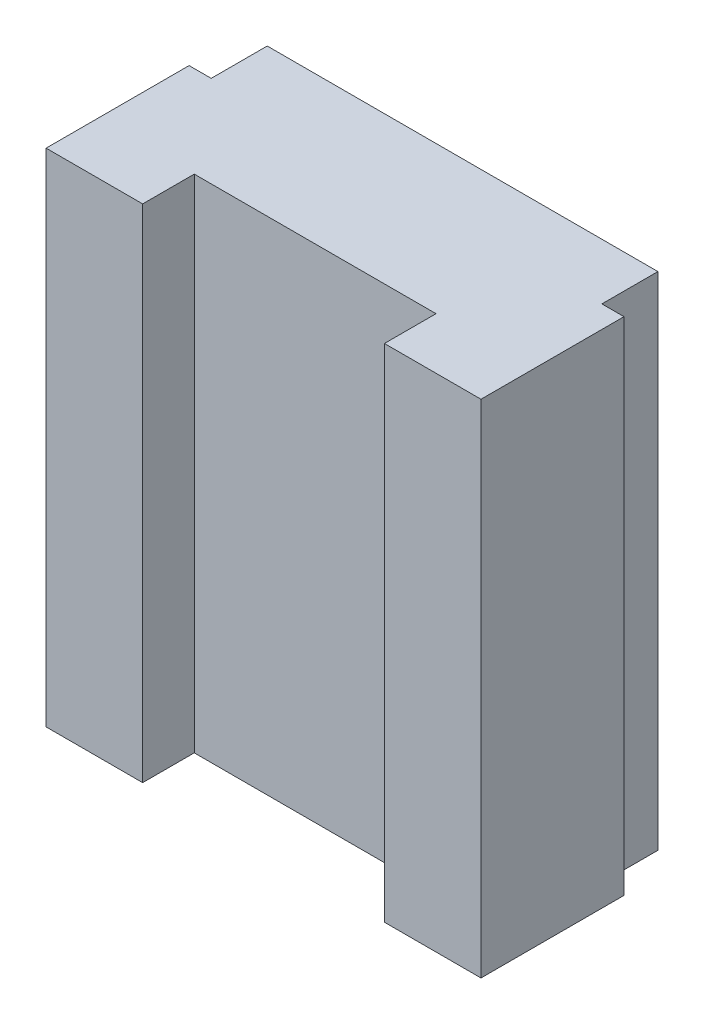
SolidWorks part; units mm, degrees
ref_plane "Front Plane" through (0, 0, 0) normal (0, 0, 1) x (1, 0, 0)
ref_plane "Top Plane" through (0, 0, 0) normal (0, 1, 0) x (1, 0, 0)
ref_plane "Right Plane" through (0, 0, 0) normal (1, 0, 0) x (0, 0, -1)
sketch "Sketch1" plane through (0, 0, 0) normal (0, 0, 1) x (1, 0, 0)
  line L1 (-14.75, 17) -> (14.75, 17)
  line L2 (-14.75, 17) -> (-14.75, -17)
  line L3 (-14.75, -17) -> (14.75, -17)
  line L4 (14.75, 17) -> (14.75, -17)
  line L5 (-14.75, 17) -> (14.75, -17) construction
  line L6 (-14.75, -17) -> (14.75, 17) construction
  point P0 (0, 0)
  dimension "D1" = 29.5
  dimension "D2" = 34
extrude "Boss-Extrude1" add sketch "Sketch1" along normal blind 13.5
sketch "Sketch2" plane through (0, 17, 0) normal (0, 1, 0) x (1, 0, 0)
  line L0 (-14.75, 0) -> (-14.75, -3.8)
  line L1 (-14.75, -13.5) -> (-14.75, 0) construction
  line L2 (-14.75, -3.8) -> (-13.25, -3.8)
  line L4 (-13.25, -3.8) -> (-13.25, 0)
  line L5 (14.75, 0) -> (-14.75, 0) construction
  line L6 (-13.25, 0) -> (-14.75, 0)
  line L7 (14.75, -13.5) -> (-14.75, -13.5) construction
  line L8 (-8.2, -10) -> (8.2, -10)
  line L9 (-8.2, -10) -> (-8.2, -13.5)
  line L10 (-8.2, -13.5) -> (8.2, -13.5)
  line L11 (8.2, -10) -> (8.2, -13.5)
  line L12 (-8.2, -10) -> (8.2, -13.5) construction
  line L13 (-8.2, -13.5) -> (8.2, -10) construction
  point P0 (0, -11.75)
  point P17 (0, 0)
  dimension "D1" = 9.7
  dimension "D2" = 1.5
  dimension "D3" = 3.5
  dimension "D4" = 16.4
extrude "Cut-Extrude1" cut sketch "Sketch2" against normal through all
mirror "Mirror1" about plane through (0, 0, 0) normal (1, 0, 0) of "Cut-Extrude1"
